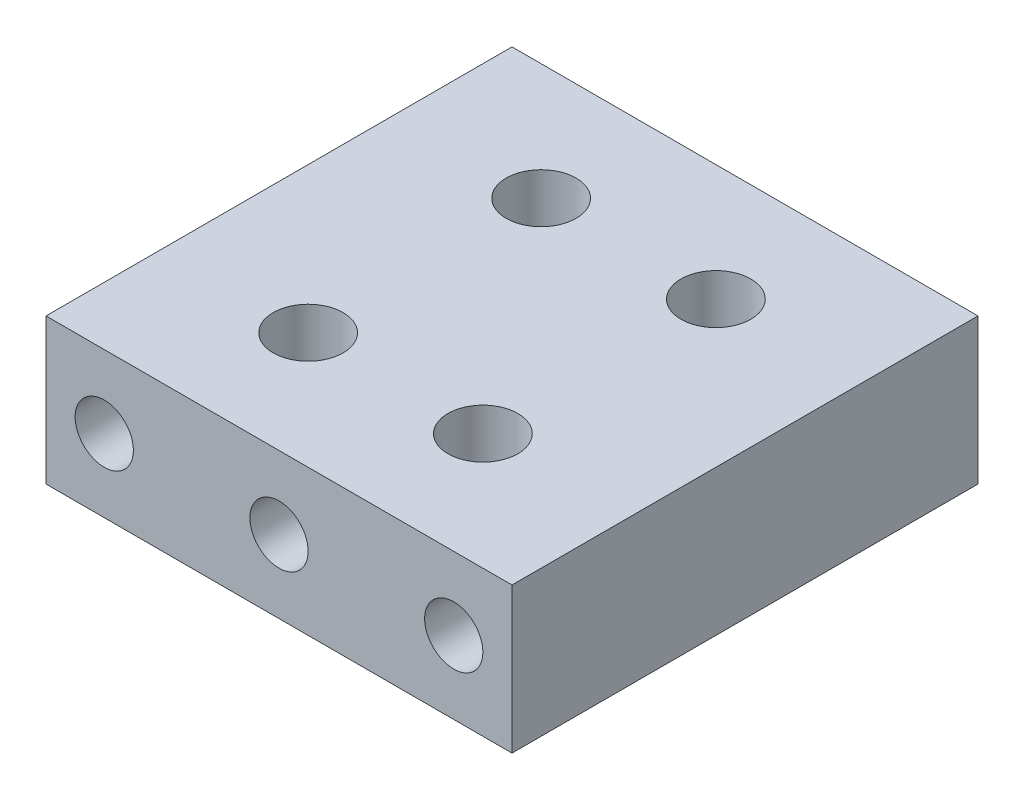
SolidWorks part; units mm, degrees
ref_plane "Front Plane" through (0, 0, 0) normal (0, 0, 1) x (1, 0, 0)
ref_plane "Top Plane" through (0, 0, 0) normal (0, 1, 0) x (1, 0, 0)
ref_plane "Right Plane" through (0, 0, 0) normal (1, 0, 0) x (0, 0, -1)
sketch "Sketch1" plane through (0, 0, 0) normal (0, 1, 0) x (1, 0, 0)
  line L1 (-25.4, 25.4) -> (25.4, 25.4)
  line L2 (-25.4, 25.4) -> (-25.4, -25.4)
  line L3 (-25.4, -25.4) -> (25.4, -25.4)
  line L4 (25.4, 25.4) -> (25.4, -25.4)
  dimension "D1" = 50.8
  dimension "D2" = 50.8
  dimension "D3" = 25.4
  dimension "D4" = 25.4
extrude "Boss-Extrude1" add sketch "Sketch1" along normal blind 15.875
sketch "Sketch2" plane through (0, 0, 25.4) normal (0, 0, 1) x (1, 0, 0)
  line L0 (-25.4, 0) -> (25.4, 0) construction
  circle A0 centre (-19.05, 7.9375) radius 3.175
  circle A1 centre (0, 7.9375) radius 3.175
  circle A2 centre (19.05, 7.9375) radius 3.175
  dimension "D1" = 6.35
  dimension "D2" = 19.05
  dimension "D3" = 19.05
  dimension "D4" = 7.9375
extrude "Cut-Extrude1" cut sketch "Sketch2" against normal through all
hole_wizard "Tap Drill for #8-32 Tap1" positions "Sketch4" profile "Sketch3" hole size "#8-32" standard "ANSI Inch" end condition through all
sketch "Sketch4" plane through (0, 15.875, 0) normal (0, 1, 0) x (1, 0, 0)
  point P0 (-9.525, -12.7)
  point P2 (-9.525, 12.7)
  point P4 (9.525, 12.7)
  point P6 (9.525, -12.7)
  point P18 (6.8361, -10.6216)
  dimension "D1" = 12.7
  dimension "D2" = 9.525
  dimension "D3" = 9.525
  dimension "D4" = 12.7
sketch "Sketch3" plane through (-9.525, 15.875, 12.7) normal (1, 0, 0) x (0, 0, 1)
  line L0 (0, 0) -> (0, 15.875)
  line L1 (0, 15.875) -> (1.7272, 15.875)
  line L2 (1.7272, 15.875) -> (1.7272, 0)
  line L5 (1.7272, 0) -> (0, 0)
  line L11 (0, -6.35) -> (0, 107.95) construction
  dimension "Thru Hole Dia." = 3.4544
  dimension "Thru Hole Depth" = 15.875
sketch "Sketch5" plane through (0, 15.875, 0) normal (0, 1, 0) x (1, 0, 0)
  circle A0 centre (-9.525, 12.7) radius 3.81
  circle A1 centre (9.525, 12.7) radius 3.81
  circle A2 centre (9.525, -12.7) radius 3.81
  circle A3 centre (-9.525, -12.7) radius 3.81
  dimension "D1" = 7.62
extrude "Cut-Extrude2" cut sketch "Sketch5" against normal blind 6.35
